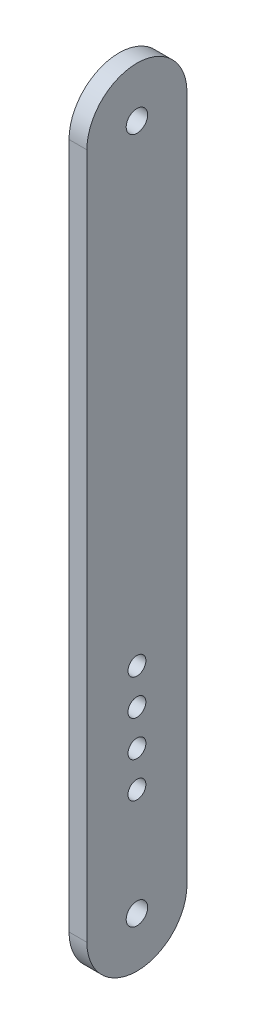
SolidWorks part; units mm, degrees
material "Acrylic (Medium-high impact)"
ref_plane "Ground" through (0, 0, 0) normal (0, 0, 1) x (1, 0, 0)
ref_plane "Right" through (0, 0, 0) normal (0, 1, 0) x (1, 0, 0)
ref_plane "Front" through (0, 0, 0) normal (1, 0, 0) x (0, 0, -1)
sketch "Sketch1" plane through (0, 0, 0) normal (1, 0, 0) x (0, 0, -1)
  line L0 (0, 0) -> (0, 96) construction
  line L1 (-7, 0) -> (-7, 96)
  line L2 (7, 0) -> (7, 96)
  arc A0 (-7, 0) -> (7, 0) centre (0, 0) ccw
  arc A1 (7, 96) -> (-7, 96) centre (0, 96) ccw
  circle A2 centre (0, 0) radius 1.5
  circle A3 centre (0, 96) radius 1.5
  circle A4 centre (0, 15) radius 1.25
  circle A5 centre (0, 20) radius 1.25
  circle A6 centre (0, 25) radius 1.25
  circle A7 centre (0, 30) radius 1.25
  point P3 (0, 48)
  dimension "D2" = 3
  dimension "D3" = 7
  dimension "D4" = 7
  dimension "D5" = 2.5
  dimension "D1" = 96
  dimension "D6" = 15
  dimension "D7" = 4
extrude "Boss-Extrude1" add sketch "Sketch1" along normal blind 2.5 contours L2 A1 L1 A0 | A3 | A2 | A5 | A6 | A7 | A4
